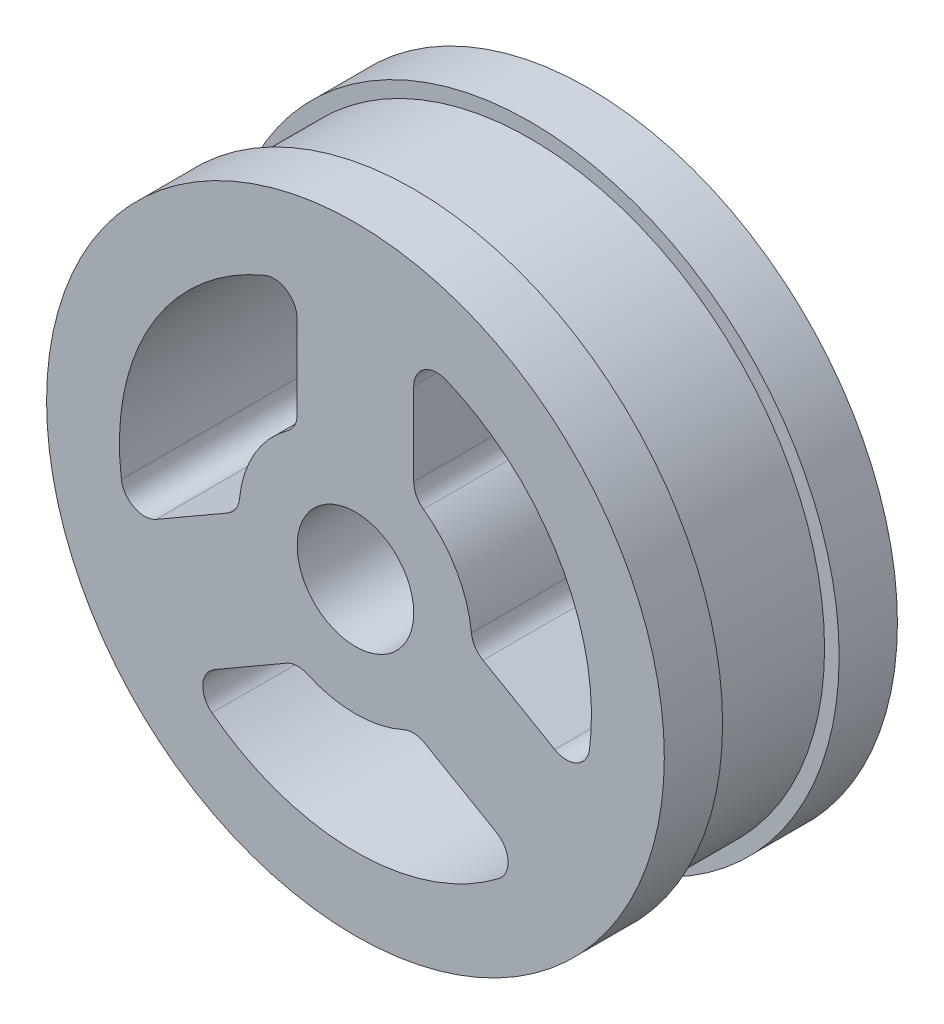
SolidWorks part; units mm, degrees
material "PE High Density"
ref_plane "Front Plane" through (0, 0, 0) normal (0, 0, 1) x (1, 0, 0)
ref_plane "Top Plane" through (0, 0, 0) normal (0, 1, 0) x (1, 0, 0)
ref_plane "Right Plane" through (0, 0, 0) normal (1, 0, 0) x (0, 0, -1)
sketch "Sketch1" plane through (0, 0, 0) normal (0, 0, 1) x (1, 0, 0)
  circle A0 centre (0, 0) radius 26.5
  dimension "D1" = 53
extrude "Boss-Extrude1" add sketch "Sketch1" along normal blind 5
sketch "Sketch2" plane through (0, 0, 5) normal (0, 0, 1) x (1, 0, 0)
  circle A0 centre (0, 0) radius 25.25
  dimension "D1" = 50.5
extrude "Boss-Extrude2" add sketch "Sketch2" along normal blind 10
sketch "Sketch3" plane through (0, 0, 15) normal (0, 0, 1) x (1, 0, 0)
  circle A1 centre (0, 0) radius 25.25
  circle A2 centre (0, 0) radius 25.25
  circle A3 centre (0, 0) radius 26.5
  circle A4 centre (0, 0) radius 26.5
  dimension "D1" = 0
  dimension "D2" = 0
extrude "Boss-Extrude3" add sketch "Sketch3" along normal blind 5 contours A4
sketch "Sketch4" plane through (0, 0, 20) normal (0, 0, 1) x (1, 0, 0)
  circle A0 centre (0, 0) radius 5
  dimension "D1" = 10
extrude "Cut-Extrude1" cut sketch "Sketch4" against normal through all
sketch "Sketch5" plane through (0, 0, 0) normal (0, 1, 0) x (1, 0, 0)
  line L0 (0, 0) -> (0, -28.6983) construction
sketch "Sketch6" plane through (0, 0, 20) normal (0, 0, 1) x (1, 0, 0)
  line L0 (0, 10) -> (0, 20.25)
  line L1 (8.6603, -5) -> (17.537, -10.125)
  line L2 (-8.6603, -5) -> (-17.537, -10.125)
  line L3 (5, 8.6603) -> (5, 19.623)
  line L4 (-5, 8.6603) -> (-5, 19.623)
  line L5 (-5, 10) -> (-5, 20.25) construction
  line L6 (5, 10) -> (5, 20.25) construction
  line L7 (10, 0) -> (19.494, -5.4814)
  line L8 (5, -8.6603) -> (14.494, -14.1416)
  line L9 (-5, -8.6603) -> (-14.494, -14.1416)
  line L10 (-10, 0) -> (-19.494, -5.4814)
  circle A0 centre (0, 0) radius 25.25 construction
  circle A3 centre (0, 0) radius 25.25
  circle A4 centre (0, 0) radius 20.25
  circle A5 centre (0, 0) radius 5 construction
  circle A6 centre (0, 0) radius 5
  circle A7 centre (0, 0) radius 10
  point P19 (0, 0)
  point P35 (0, 0)
  dimension "D7" = 35.074
  dimension "D8" = 10
  dimension "D9" = 10
  dimension "D10" = 28.988
  dimension "D1" = 3
  dimension "D2" = 5
  dimension "D3" = 5
  dimension "D4" = 5
  dimension "D5" = 5
  dimension "D6" = 3
extrude "Cut-Extrude2" cut sketch "Sketch6" against normal through all contours A7 L4 A4 L10 | A7 L9 A4 L8 | A7 L7 A4 L3
fillet "Fillet1" radius 2 12 edges at (14.494, -14.1416, 10) (-14.494, -14.1416, 10) (5, -8.6603, 10) (-5, -8.6603, 10) (-19.494, -5.4814, 10) (-10, 0, 10) (-5, 8.6603, 10) (5, 19.623, 10) (10, 0, 10) (5, 8.6603, 10) (19.494, -5.4814, 10) (-5, 19.623, 10)
